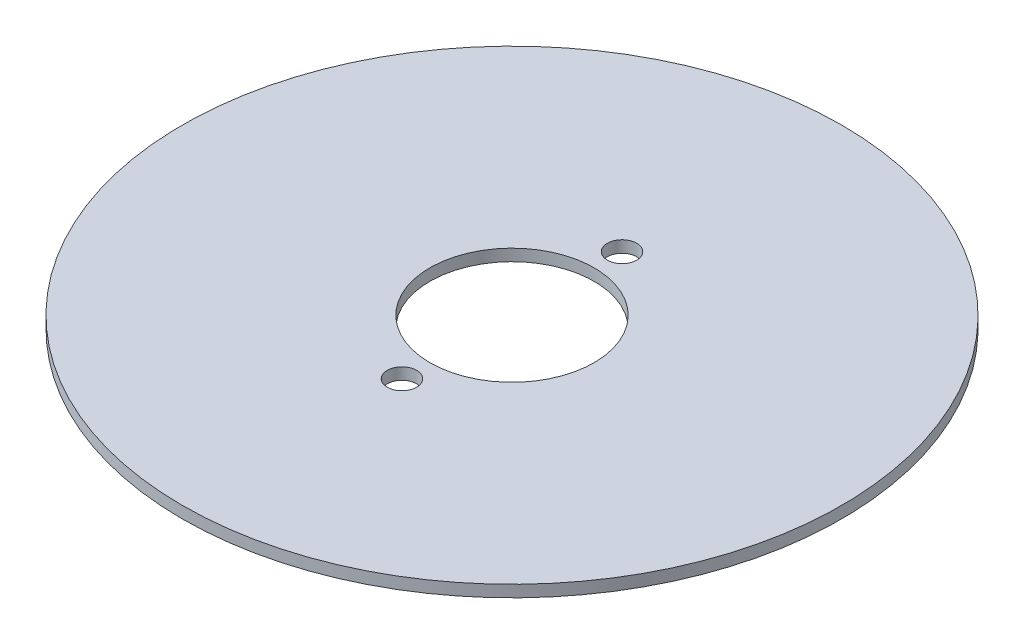
SolidWorks part; units mm, degrees
ref_plane "Front Plane" through (0, 0, 0) normal (0, 0, 1) x (1, 0, 0)
ref_plane "Top Plane" through (0, 0, 0) normal (0, 1, 0) x (1, 0, 0)
ref_plane "Right Plane" through (0, 0, 0) normal (1, 0, 0) x (0, 0, -1)
sketch "Sketch1" plane through (0, 0, 0) normal (0, 1, 0) x (1, 0, 0)
  line L0 (0, 18.75) -> (0, -18.75) construction
  circle A0 centre (0, 0) radius 56.15
  circle A1 centre (0, 0) radius 18.75 construction
  circle A2 centre (0, 18.75) radius 2.5
  circle A3 centre (0, -18.75) radius 2.5
  circle A4 centre (0, 0) radius 14
  point P7 (0, 0)
  dimension "D1" = 112.3
  dimension "D2" = 37.5
  dimension "D3" = 5
  dimension "D4" = 5
  dimension "D5" = 28
extrude "Boss-Extrude1" add sketch "Sketch1" along normal blind 2
